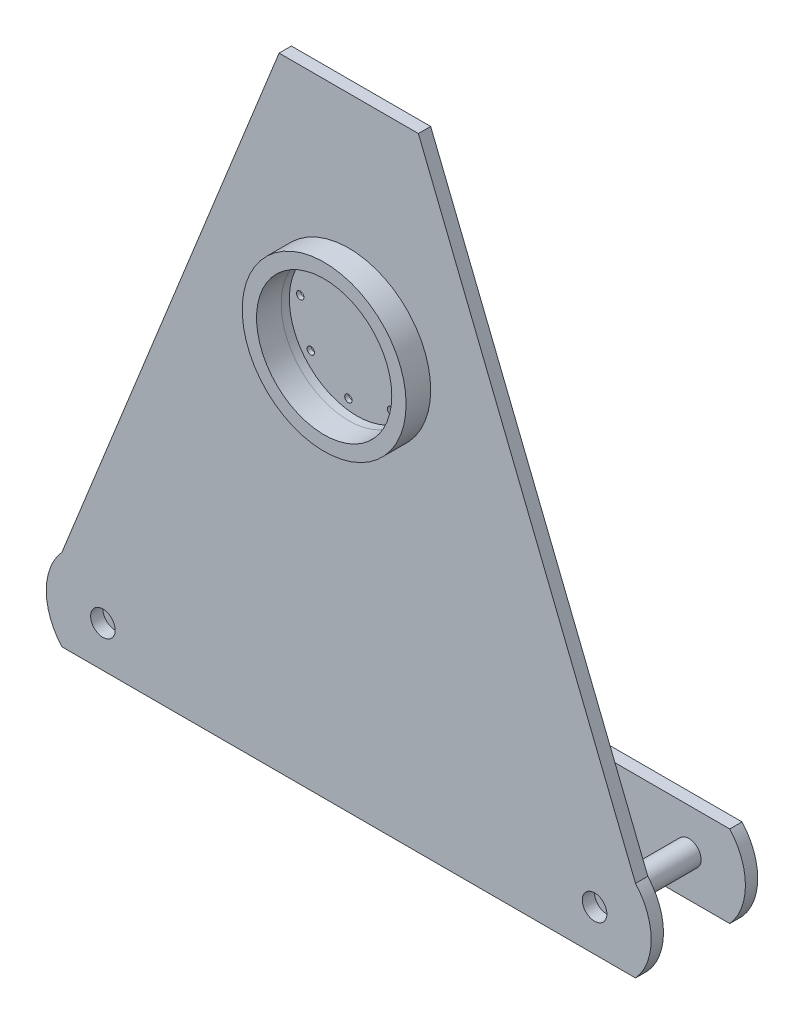
SolidWorks part; units mm, degrees
ref_plane "Front Plane" through (0, 0, 0) normal (0, 0, 1) x (1, 0, 0)
ref_plane "Top Plane" through (0, 0, 0) normal (0, 1, 0) x (1, 0, 0)
ref_plane "Right Plane" through (0, 0, 0) normal (1, 0, 0) x (0, 0, -1)
sketch "Sketch1" plane through (0, 0, 0) normal (0, 0, 1) x (1, 0, 0)
  line L1 (-350, -50) -> (350, -50)
  line L2 (-350, -50) -> (-350, 50)
  line L3 (-350, 50) -> (350, 50)
  line L4 (350, -50) -> (350, 50)
  line L5 (-350, -50) -> (350, 50) construction
  line L6 (-350, 50) -> (350, -50) construction
  arc A0 (350, 50) -> (350, -50) centre (294.0983, 0) cw
  arc A1 (-350, 50) -> (-350, -50) centre (-294.0983, 0) ccw
  circle A2 centre (-300, 0) radius 15
  circle A3 centre (300, 0) radius 15
  point P0 (0, 0)
  dimension "D1" = 75
  dimension "D4" = 75
  dimension "D5" = 30
  dimension "D2" = 700
  dimension "D3" = 100
  dimension "D6" = 300
  dimension "D7" = 300
extrude "Boss-Extrude1" add sketch "Sketch1" along normal blind 15 contours L1 L4 L3 L2 | L2 A1 | A0 L4
pattern_linear "LPattern1" count 2 spacing 115 along (0, 0, 1) of bodies 101
sketch "Sketch3" plane through (0, 0, 15) normal (0, 0, 1) x (1, 0, 0)
  circle A0 centre (-300, 0) radius 15 construction
  circle A1 centre (-300, 0) radius 15
  circle A2 centre (300, 0) radius 15 construction
  circle A3 centre (300, 0) radius 15
extrude "Boss-Extrude2" add sketch "Sketch3" along normal blind 100 separate body
sketch "Sketch4" plane through (0, 0, 130) normal (0, 0, 1) x (1, 0, 0)
  line L0 (0, 0) -> (0, 685.803) construction
  line L1 (-350, 50) -> (-85, 710)
  line L2 (-85, 710) -> (85, 710)
  line L3 (350, 50) -> (85, 710)
  line L4 (-350, 50) -> (350, 50)
  line L5 (-350, -50) -> (350, -50) construction
  point P8 (0, 710)
  dimension "D1" = 760
  dimension "D2" = 170
extrude "Boss-Extrude3" add sketch "Sketch4" against normal up to surface (15 mm away) up to face at (315, 0, 115)
sketch "Sketch5" plane through (0, 0, 130) normal (0, 0, 1) x (1, 0, 0)
  line L0 (0, 710) -> (0, 446.48) construction
  line L1 (85, 710) -> (-85, 710) construction
  circle A0 centre (0, 446.48) radius 82.5
  dimension "D2" = 165
  dimension "D1" = 263.52
extrude "Cut-Extrude1" cut sketch "Sketch5" against normal through all
sketch "Sketch6" plane through (0, 0, 115) normal (0, 0, 1) x (1, 0, 0)
  circle A1 centre (0, 446.48) radius 100
  dimension "D1" = 200
extrude "Boss-Extrude4" add sketch "Sketch6" along normal blind 5
sketch "Sketch7" plane through (0, 0, 130) normal (0, 0, 1) x (1, 0, 0)
  circle A0 centre (0, 446.48) radius 82.5
  circle A1 centre (0, 446.48) radius 82.5 construction
  circle A2 centre (0, 446.48) radius 100
  dimension "D1" = 200
extrude "Boss-Extrude5" add sketch "Sketch7" along normal blind 30 separate body
sketch "Sketch8" plane through (0, 0, 130) normal (0, 0, 1) x (1, 0, 0)
  line L0 (300, 0) -> (-300, 0)
  line L1 (0, -2569.4317) -> (0, 3726.1686) construction
  point P4 (0, 0)
sketch "Sketch9" plane through (0, 0, 120) normal (0, 0, 1) x (1, 0, 0)
  circle A0 centre (0, 446.48) radius 70
  circle A1 centre (0, 446.48) radius 82.5 construction
  circle A2 centre (0, 446.48) radius 82.5
  circle A3 centre (-56.3102, 404.8968) radius 4.5
  dimension "D1" = 140
  dimension "D2" = 9
extrude "Cut-Extrude2" cut sketch "Sketch9" against normal through all contours A3
pattern_circular "CirPattern1" count 8 over 360 about axis through (0, 446.48, 0) along (0, 0, 1) of "Cut-Extrude2"
